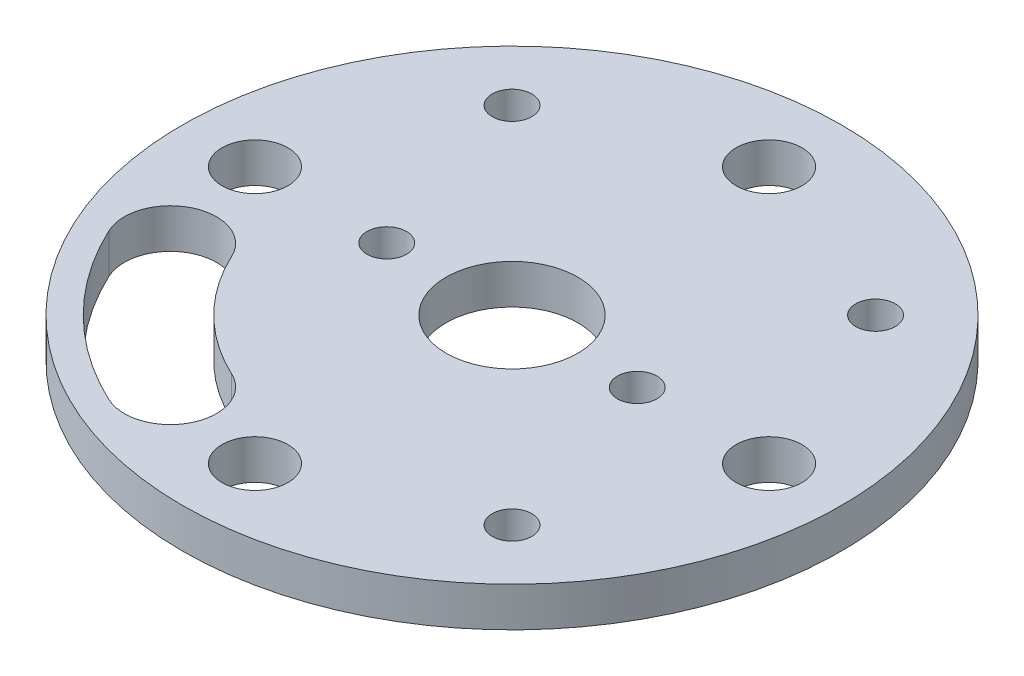
SolidWorks part; units mm, degrees
ref_plane "前基準面" through (0, 0, 0) normal (0, 0, 1) x (1, 0, 0)
ref_plane "上基準面" through (0, 0, 0) normal (0, 1, 0) x (1, 0, 0)
ref_plane "右基準面" through (0, 0, 0) normal (1, 0, 0) x (0, 0, -1)
sketch "草圖1" plane through (0, 0, 0) normal (0, 1, 0) x (1, 0, 0)
  line L0 (-9.5, 0) -> (9.5, 0) construction
  line L1 (0, 14) -> (0, 25) construction
  line L2 (0, -14) -> (0, -25) construction
  line L3 (-11.3137, -11.3137) -> (0, 0) construction
  circle A0 centre (0, 0) radius 5
  circle A1 centre (-9.5, 0) radius 1.5
  circle A2 centre (9.5, 0) radius 1.5
  circle A3 centre (0, 0) radius 25
  circle A4 centre (0, 19.5) radius 2.5
  circle A5 centre (19.5, 0) radius 2.5
  circle A6 centre (0, 0) radius 14 construction
  circle A7 centre (0, -19.5) radius 2.5
  circle A8 centre (-19.5, 0) radius 2.5
  arc A9 (-19.5, 0) -> (0, -19.5) centre (0, 0) ccw construction
  arc A10 (-20.8451, -9.7202) -> (-9.7202, -20.8451) centre (0, 0) ccw
  arc A11 (-14.5009, -6.7619) -> (-6.7619, -14.5009) centre (0, 0) ccw
  arc A12 (-20.8451, -9.7202) -> (-14.5009, -6.7619) centre (-17.673, -8.2411) cw
  arc A13 (-6.7619, -14.5009) -> (-9.7202, -20.8451) centre (-8.2411, -17.673) cw
  circle A14 centre (0, 0) radius 19.5 construction
  circle A15 centre (-13.7886, 13.7886) radius 1.5
  circle A16 centre (13.7886, 13.7886) radius 1.5
  circle A17 centre (13.7886, -13.7886) radius 1.5
  dimension "D1" = 3
  dimension "D3" = 10
  dimension "D4" = 50
  dimension "D5" = 28
  dimension "D6" = 5
  dimension "D8" = 7
  dimension "D11" = 3
  dimension "D2" = 19
  dimension "D9" = 40
  dimension "D10" = 45
  dimension "D12" = 45
  dimension "D13" = 45
  dimension "D14" = 45
  dimension "D7" = 4
extrude "填料-伸長1" add sketch "草圖1" along normal blind 3
